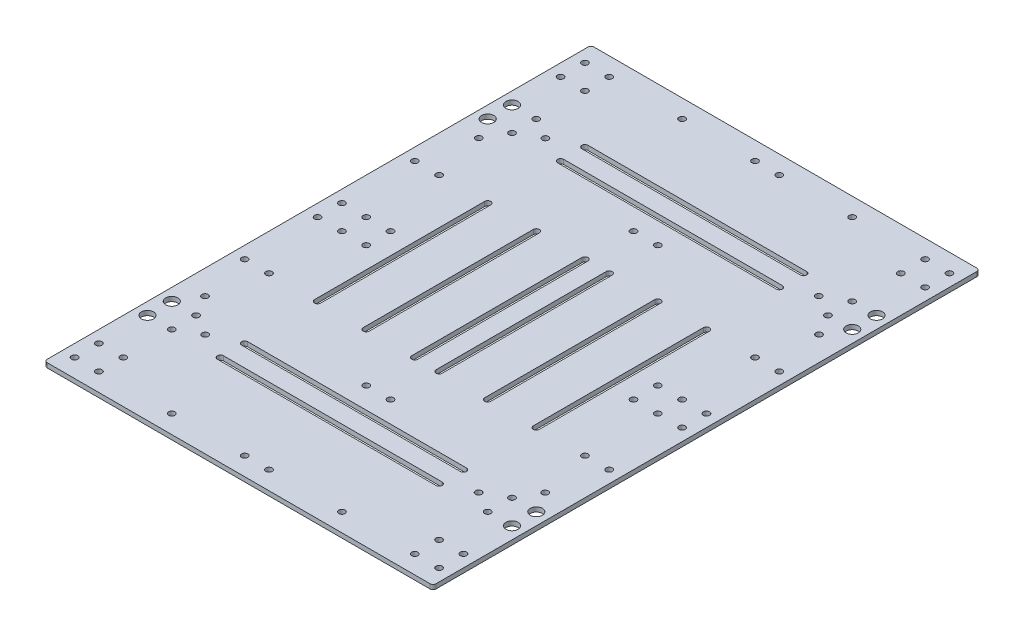
SolidWorks part; units mm, degrees
ref_plane "Front Plane" through (0, 0, 0) normal (0, 0, 1) x (1, 0, 0)
ref_plane "Top Plane" through (0, 0, 0) normal (0, 1, 0) x (1, 0, 0)
ref_plane "Right Plane" through (0, 0, 0) normal (1, 0, 0) x (0, 0, -1)
sketch "Sketch1" plane through (0, 0, 0) normal (0, 1, 0) x (1, 0, 0)
  line L1 (-128, -180) -> (128, -180)
  line L2 (-128, -180) -> (-128, 180)
  line L3 (-128, 180) -> (128, 180)
  line L4 (128, -180) -> (128, 180)
  point P4 (-128, 0)
  point P6 (0, 180)
  dimension "D1" = 256
  dimension "D2" = 360
extrude "Boss-Extrude1" add sketch "Sketch1" against normal blind 3
fillet "Fillet1" radius 2 4 edges at (128, -1.5, -180) (-128, -1.5, -180) (-128, -1.5, 180) (128, -1.5, 180)
sketch "Sketch2" plane through (0, 0, 0) normal (0, 1, 0) x (1, 0, 0)
  line L0 (-1000, 0) -> (49000, 0) construction
  line L1 (0, -1000) -> (0, 49000) construction
  circle A0 centre (-120, 104) radius 4
  circle A1 centre (-120, 120) radius 4
  circle A2 centre (120, 104) radius 4
  circle A3 centre (120, 120) radius 4
  circle A4 centre (120, -104) radius 4
  circle A5 centre (120, -120) radius 4
  circle A6 centre (-120, -120) radius 4
  circle A7 centre (-120, -104) radius 4
  point P21 (0, 0)
  dimension "D1" = 8
  dimension "D4" = 8
  dimension "D2" = 208
  dimension "D3" = 240
  dimension "D5" = 240
  dimension "D6" = 240
extrude "Cut-Extrude2" cut sketch "Sketch2" against normal through all
sketch "Sketch4" plane through (0, 0, 0) normal (0, 1, 0) x (1, 0, 0)
  line L0 (-1000, 0) -> (49000, 0) construction
  line L1 (0, -1000) -> (0, 49000) construction
  circle A0 centre (-120, 168) radius 2.05
  circle A1 centre (-104, 168) radius 2.05
  circle A2 centre (-88, 168) radius 2.05 [skipped]
  circle A3 centre (-72, 168) radius 2.05 [skipped]
  circle A4 centre (-56, 168) radius 2.05
  circle A5 centre (-40, 168) radius 2.05 [skipped]
  circle A6 centre (-24, 168) radius 2.05 [skipped]
  circle A7 centre (-8, 168) radius 2.05
  circle A8 centre (-104, 152) radius 2.05
  circle A9 centre (-88, 152) radius 2.05 [skipped]
  circle A10 centre (-72, 152) radius 2.05 [skipped]
  circle A11 centre (-56, 152) radius 2.05 [skipped]
  circle A12 centre (-40, 152) radius 2.05 [skipped]
  circle A13 centre (-24, 152) radius 2.05 [skipped]
  circle A14 centre (-8, 152) radius 2.05 [skipped]
  circle A15 centre (-104, 136) radius 2.05 [skipped]
  circle A16 centre (-88, 136) radius 2.05 [skipped]
  circle A17 centre (-72, 136) radius 2.05 [skipped]
  circle A18 centre (-56, 136) radius 2.05 [skipped]
  circle A19 centre (-40, 136) radius 2.05 [skipped]
  circle A20 centre (-24, 136) radius 2.05 [skipped]
  circle A21 centre (-8, 136) radius 2.05 [skipped]
  circle A22 centre (-104, 120) radius 2.05
  circle A23 centre (-88, 120) radius 2.05 [skipped]
  circle A24 centre (-72, 120) radius 2.05 [skipped]
  circle A25 centre (-56, 120) radius 2.05 [skipped]
  circle A26 centre (-40, 120) radius 2.05 [skipped]
  circle A27 centre (-24, 120) radius 2.05 [skipped]
  circle A28 centre (-8, 120) radius 2.05 [skipped]
  circle A29 centre (-104, 104) radius 2.05
  circle A30 centre (-88, 104) radius 2.05 [skipped]
  circle A31 centre (-72, 104) radius 2.05 [skipped]
  circle A32 centre (-56, 104) radius 2.05 [skipped]
  circle A33 centre (-40, 104) radius 2.05 [skipped]
  circle A34 centre (-24, 104) radius 2.05 [skipped]
  circle A35 centre (-8, 104) radius 2.05 [skipped]
  circle A36 centre (-104, 88) radius 2.05 [skipped]
  circle A37 centre (-88, 88) radius 2.05 [skipped]
  circle A38 centre (-72, 88) radius 2.05 [skipped]
  circle A39 centre (-56, 88) radius 2.05 [skipped]
  circle A40 centre (-40, 88) radius 2.05 [skipped]
  circle A41 centre (-24, 88) radius 2.05 [skipped]
  circle A42 centre (-8, 88) radius 2.05
  circle A43 centre (-104, 72) radius 2.05 [skipped]
  circle A44 centre (-88, 72) radius 2.05 [skipped]
  circle A45 centre (-72, 72) radius 2.05 [skipped]
  circle A46 centre (-56, 72) radius 2.05 [skipped]
  circle A47 centre (-40, 72) radius 2.05 [skipped]
  circle A48 centre (-24, 72) radius 2.05 [skipped]
  circle A49 centre (-8, 72) radius 2.05 [skipped]
  circle A50 centre (-104, 56) radius 2.05
  circle A51 centre (-88, 56) radius 2.05 [skipped]
  circle A52 centre (-72, 56) radius 2.05 [skipped]
  circle A53 centre (-56, 56) radius 2.05 [skipped]
  circle A54 centre (-40, 56) radius 2.05 [skipped]
  circle A55 centre (-24, 56) radius 2.05 [skipped]
  circle A56 centre (-8, 56) radius 2.05 [skipped]
  circle A57 centre (-104, 40) radius 2.05 [skipped]
  circle A58 centre (-88, 40) radius 2.05 [skipped]
  circle A59 centre (-72, 40) radius 2.05 [skipped]
  circle A60 centre (-56, 40) radius 2.05 [skipped]
  circle A61 centre (-40, 40) radius 2.05 [skipped]
  circle A62 centre (-24, 40) radius 2.05 [skipped]
  circle A63 centre (-8, 40) radius 2.05 [skipped]
  circle A64 centre (-104, 24) radius 2.05 [skipped]
  circle A65 centre (-88, 24) radius 2.05 [skipped]
  circle A66 centre (-72, 24) radius 2.05 [skipped]
  circle A67 centre (-56, 24) radius 2.05 [skipped]
  circle A68 centre (-40, 24) radius 2.05 [skipped]
  circle A69 centre (-24, 24) radius 2.05 [skipped]
  circle A70 centre (-8, 24) radius 2.05 [skipped]
  circle A71 centre (-104, 8) radius 2.05
  circle A72 centre (-88, 8) radius 2.05
  circle A73 centre (-72, 8) radius 2.05 [skipped]
  circle A74 centre (-56, 8) radius 2.05 [skipped]
  circle A75 centre (-40, 8) radius 2.05 [skipped]
  circle A76 centre (-24, 8) radius 2.05 [skipped]
  circle A77 centre (-8, 8) radius 2.05 [skipped]
  circle A78 centre (-120, 152) radius 2.05
  circle A79 centre (-120, 136) radius 2.05 [skipped]
  circle A80 centre (-120, 120) radius 2.05
  circle A81 centre (-120, 104) radius 2.05
  circle A82 centre (-120, 88) radius 2.05 [skipped]
  circle A83 centre (-120, 72) radius 2.05 [skipped]
  circle A84 centre (-120, 56) radius 2.05
  circle A85 centre (-120, 40) radius 2.05 [skipped]
  circle A86 centre (-120, 24) radius 2.05 [skipped]
  circle A87 centre (-120, 8) radius 2.05
  circle A88 centre (120, 8) radius 2.05
  circle A89 centre (120, 56) radius 2.05
  circle A90 centre (120, 104) radius 2.05
  circle A91 centre (120, 120) radius 2.05
  circle A92 centre (120, 152) radius 2.05
  circle A93 centre (88, 8) radius 2.05
  circle A94 centre (104, 8) radius 2.05
  circle A95 centre (104, 56) radius 2.05
  circle A96 centre (8, 88) radius 2.05
  circle A97 centre (104, 104) radius 2.05
  circle A98 centre (104, 120) radius 2.05
  circle A99 centre (104, 152) radius 2.05
  circle A100 centre (8, 168) radius 2.05
  circle A101 centre (56, 168) radius 2.05
  circle A102 centre (104, 168) radius 2.05
  circle A103 centre (120, 168) radius 2.05
  circle A104 centre (120, -168) radius 2.05
  circle A105 centre (104, -168) radius 2.05
  circle A106 centre (56, -168) radius 2.05
  circle A107 centre (8, -168) radius 2.05
  circle A108 centre (104, -152) radius 2.05
  circle A109 centre (104, -120) radius 2.05
  circle A110 centre (104, -104) radius 2.05
  circle A111 centre (8, -88) radius 2.05
  circle A112 centre (104, -56) radius 2.05
  circle A113 centre (104, -8) radius 2.05
  circle A114 centre (88, -8) radius 2.05
  circle A115 centre (120, -152) radius 2.05
  circle A116 centre (120, -120) radius 2.05
  circle A117 centre (120, -104) radius 2.05
  circle A118 centre (120, -56) radius 2.05
  circle A119 centre (120, -8) radius 2.05
  circle A120 centre (-120, -8) radius 2.05
  circle A121 centre (-120, -56) radius 2.05
  circle A122 centre (-120, -104) radius 2.05
  circle A123 centre (-120, -120) radius 2.05
  circle A124 centre (-120, -152) radius 2.05
  circle A125 centre (-88, -8) radius 2.05
  circle A126 centre (-104, -8) radius 2.05
  circle A127 centre (-104, -56) radius 2.05
  circle A128 centre (-8, -88) radius 2.05
  circle A129 centre (-104, -104) radius 2.05
  circle A130 centre (-104, -120) radius 2.05
  circle A131 centre (-104, -152) radius 2.05
  circle A132 centre (-8, -168) radius 2.05
  circle A133 centre (-56, -168) radius 2.05
  circle A134 centre (-104, -168) radius 2.05
  circle A135 centre (-120, -168) radius 2.05
  dimension "D1" = 4.1
  dimension "D2" = 240
  dimension "D3" = 336
  dimension "D4" = 8
  dimension "D5" = 11
extrude "Cut-Extrude3" cut sketch "Sketch4" against normal through all
sketch "Sketch5" plane through (0, 0, 0) normal (0, 1, 0) x (1, 0, 0)
  line L0 (-1000, 0) -> (49000, 0) construction
  line L1 (0, -1000) -> (0, 49000) construction
  circle A0 centre (-112, 90.15) radius 2.05
  circle A1 centre (-90, 112) radius 2.05
  circle A2 centre (112, 90.15) radius 2.05
  circle A3 centre (90, 112) radius 2.05
  circle A4 centre (112, -90.15) radius 2.05
  circle A5 centre (90, -112) radius 2.05
  circle A6 centre (-90, -112) radius 2.05
  circle A7 centre (-112, -90.15) radius 2.05
  point P13 (112, -90.15)
  point P14 (90, -112)
  point P15 (-90, -112)
  point P16 (-112, -90.15)
  point P17 (0, 0)
  point P18 (0, 0)
  dimension "D1" = 4.1
  dimension "D2" = 4.1
  dimension "D3" = 180.3
  dimension "D4" = 224
  dimension "D5" = 180
  dimension "D6" = 224
extrude "Cut-Extrude4" cut sketch "Sketch5" against normal through all
sketch "Sketch6" plane through (0, 0, 0) normal (0, 1, 0) x (1, 0, 0)
  line L0 (-72, 120) -> (72, 120) construction
  line L1 (-72, 122) -> (72, 122)
  line L2 (-72, 118) -> (72, 118)
  line L3 (-72, 104) -> (72, 104) construction
  line L4 (-72, 106) -> (72, 106)
  line L5 (-72, 102) -> (72, 102)
  line L6 (-8, -56) -> (-8, 56) construction
  line L7 (-10, -56) -> (-10, 56)
  line L8 (-6, -56) -> (-6, 56)
  line L9 (-40, -56) -> (-40, 56) construction
  line L10 (-42, -56) -> (-42, 56)
  line L11 (-38, -56) -> (-38, 56)
  line L12 (-72, -56) -> (-72, 56) construction
  line L13 (-74, -56) -> (-74, 56)
  line L14 (-70, -56) -> (-70, 56)
  line L15 (-1000, 0) -> (49000, 0) construction
  line L16 (0, -1000) -> (0, 49000) construction
  line L17 (-72, -104) -> (72, -104) construction
  line L18 (-72, -106) -> (72, -106)
  line L19 (-72, -102) -> (72, -102)
  line L20 (-72, -120) -> (72, -120) construction
  line L21 (-72, -122) -> (72, -122)
  line L22 (-72, -118) -> (72, -118)
  line L23 (72, -56) -> (72, 56) construction
  line L24 (74, -56) -> (74, 56)
  line L25 (70, -56) -> (70, 56)
  line L26 (40, -56) -> (40, 56) construction
  line L27 (42, -56) -> (42, 56)
  line L28 (38, -56) -> (38, 56)
  line L29 (8, -56) -> (8, 56) construction
  line L30 (10, -56) -> (10, 56)
  line L31 (6, -56) -> (6, 56)
  arc A0 (-72, 122) -> (-72, 118) centre (-72, 120) ccw
  arc A1 (72, 118) -> (72, 122) centre (72, 120) ccw
  arc A2 (-72, 106) -> (-72, 102) centre (-72, 104) ccw
  arc A3 (72, 102) -> (72, 106) centre (72, 104) ccw
  arc A4 (-10, -56) -> (-6, -56) centre (-8, -56) ccw
  arc A5 (-6, 56) -> (-10, 56) centre (-8, 56) ccw
  arc A6 (-42, -56) -> (-38, -56) centre (-40, -56) ccw
  arc A7 (-38, 56) -> (-42, 56) centre (-40, 56) ccw
  arc A8 (-74, -56) -> (-70, -56) centre (-72, -56) ccw
  arc A9 (-70, 56) -> (-74, 56) centre (-72, 56) ccw
  arc A10 (-72, -106) -> (-72, -102) centre (-72, -104) cw
  arc A11 (72, -102) -> (72, -106) centre (72, -104) cw
  arc A12 (-72, -122) -> (-72, -118) centre (-72, -120) cw
  arc A13 (72, -118) -> (72, -122) centre (72, -120) cw
  arc A14 (74, -56) -> (70, -56) centre (72, -56) cw
  arc A15 (70, 56) -> (74, 56) centre (72, 56) cw
  arc A16 (42, -56) -> (38, -56) centre (40, -56) cw
  arc A17 (38, 56) -> (42, 56) centre (40, 56) cw
  arc A18 (10, -56) -> (6, -56) centre (8, -56) cw
  arc A19 (6, 56) -> (10, 56) centre (8, 56) cw
  point P2 (0, 120)
  point P7 (0, 104)
  point P16 (-8, 0)
  point P23 (-40, 0)
  point P28 (-72, 0)
  point P41 (0, -104)
  point P49 (0, -120)
  point P56 (72, 0)
  point P63 (40, 0)
  point P70 (8, 0)
  dimension "D1" = 4
  dimension "D2" = 144
  dimension "D3" = 4
  dimension "D4" = 144
  dimension "D5" = 4
  dimension "D6" = 112
  dimension "D7" = 4
  dimension "D8" = 104
  dimension "D9" = 4
  dimension "D10" = 120
  dimension "D11" = 8
  dimension "D12" = 40
  dimension "D13" = 72
extrude "Cut-Extrude5" cut sketch "Sketch6" against normal through all
